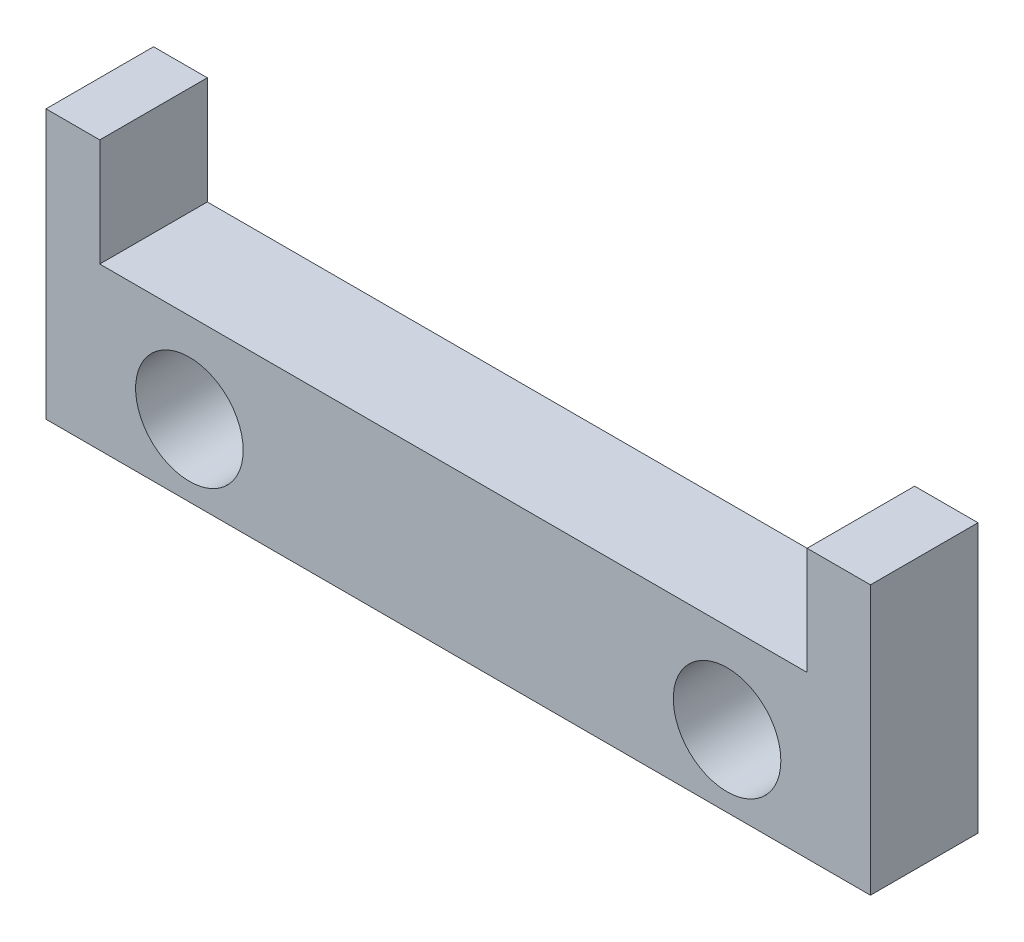
SolidWorks part; units mm, degrees
ref_plane "Plan de face" through (0, 0, 0) normal (0, 0, 1) x (1, 0, 0)
ref_plane "Plan de dessus" through (0, 0, 0) normal (0, 1, 0) x (1, 0, 0)
ref_plane "Plan de droite" through (0, 0, 0) normal (1, 0, 0) x (0, 0, -1)
sketch "Esquisse1" plane through (0, 0, 0) normal (0, 0, 1) x (1, 0, 0)
  line L0 (-23, 0) -> (23, 0)
  line L1 (23, 0) -> (23, 15)
  line L2 (-23, 15) -> (-20, 15)
  line L3 (-20, 15) -> (-20, 9)
  line L4 (-20, 9) -> (19.4646, 9)
  line L5 (19.4646, 9) -> (19.4646, 15)
  line L6 (19.4646, 15) -> (23, 15)
  line L11 (-23, 15) -> (-23, 0)
  line L12 (0, 0) -> (0, 32.85) construction
  line L13 (17.3187, 4) -> (-26.4652, 4) construction
  circle A0 centre (-15, 4) radius 3
  circle A1 centre (15, 4) radius 3
  point P5 (15, 4.2749)
  dimension "D6" = 6
  dimension "D1" = 46
  dimension "D2" = 3
  dimension "D3" = 6
  dimension "D4" = 5
  dimension "D5" = 15
  dimension "D8" = 15
extrude "Boss.-Extru.1" add sketch "Esquisse1" along normal blind 6
